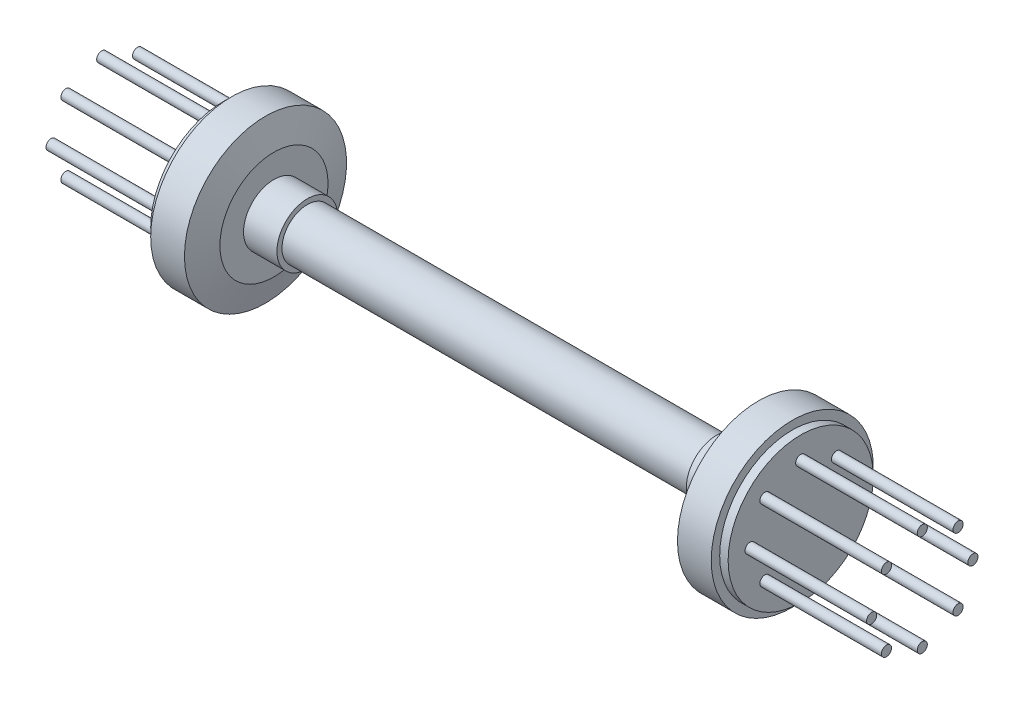
SolidWorks part; units mm, degrees
ref_plane "Front Plane" through (0, 0, 0) normal (0, 0, 1) x (1, 0, 0)
ref_plane "Top Plane" through (0, 0, 0) normal (0, 1, 0) x (1, 0, 0)
ref_plane "Right Plane" through (0, 0, 0) normal (1, 0, 0) x (0, 0, -1)
sketch "Sketch1" plane through (0, 0, 0) normal (0, 0, 1) x (1, 0, 0)
  line L0 (-1250, 0) -> (1250, 0) construction
  line L1 (-855, 0) -> (-855, 215)
  line L2 (-855, 215) -> (-830, 215)
  line L3 (-830, 215) -> (-830, 240)
  line L4 (-830, 240) -> (-730, 240)
  line L5 (-730, 240) -> (-705, 160)
  line L6 (-705, 160) -> (-705, 90)
  line L7 (-705, 90) -> (-606.1562, 90)
  line L8 (-606.1562, 90) -> (-606.1562, 75)
  line L9 (-606.1562, 75) -> (-129.9038, 75)
  line L10 (-855, 0) -> (855, 0)
  line L11 (606.1562, 75) -> (129.9038, 75)
  line L12 (606.1562, 90) -> (606.1562, 75)
  line L13 (705, 90) -> (606.1562, 90)
  line L14 (705, 160) -> (705, 90)
  line L15 (730, 240) -> (705, 160)
  line L16 (830, 240) -> (730, 240)
  line L17 (830, 215) -> (830, 240)
  line L18 (855, 215) -> (830, 215)
  line L19 (855, 0) -> (855, 215)
  line L20 (-129.9038, 75) -> (129.9038, 75)
  dimension "D1" = 2500
  dimension "D2" = 215
  dimension "D3" = 25
  dimension "D4" = 100
  dimension "D5" = 395
  dimension "D7" = 75
  dimension "D8" = 25
  dimension "D9" = 25
  dimension "D10" = 15
  dimension "D11" = 70
revolve "Revolve1" add sketch "Sketch1" angle 360 about L0
sketch "Sketch2" plane through (-855, 0, 0) normal (-1, 0, 0) x (0, 0, 1)
  circle A0 centre (0, 150) radius 15
  circle A1 centre (106.066, 106.066) radius 15
  circle A2 centre (150, 0) radius 15
  circle A3 centre (106.066, -106.066) radius 15
  circle A4 centre (0, -150) radius 15
  circle A5 centre (-106.066, -106.066) radius 15
  circle A6 centre (-150, 0) radius 15
  circle A7 centre (-106.066, 106.066) radius 15
  dimension "D1" = 30
  dimension "D2" = 150
  dimension "D3" = 8
extrude "Boss-Extrude1" add sketch "Sketch2" along normal blind 360
mirror "Mirror1" about plane through (0, 0, 0) normal (1, 0, 0) of "Boss-Extrude1"
